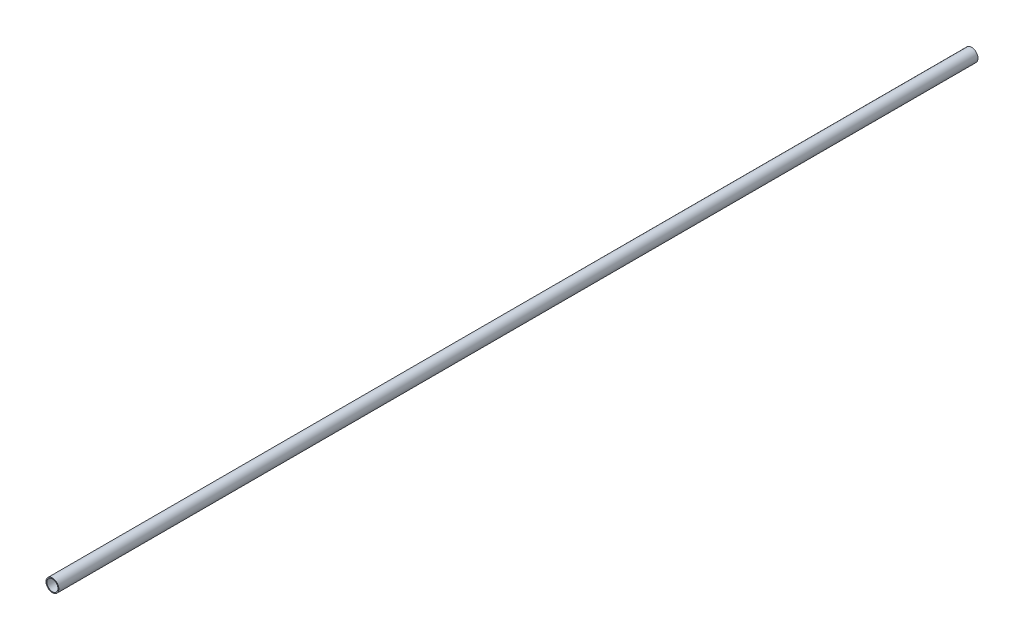
SolidWorks part; units mm, degrees
material "Poltrusion Carbon Fiber"
ref_plane "Front Plane" through (0, 0, 0) normal (0, 0, 1) x (1, 0, 0)
ref_plane "Top Plane" through (0, 0, 0) normal (0, 1, 0) x (1, 0, 0)
ref_plane "Right Plane" through (0, 0, 0) normal (1, 0, 0) x (0, 0, -1)
sketch "Эскиз1" plane through (0, 0, 0) normal (0, 0, 1) x (1, 0, 0)
  circle A0 centre (0, 0) radius 7
  circle A1 centre (0, 0) radius 6
  dimension "D1" = 14
  dimension "D2" = 1
extrude "Бобышка-Вытянуть1" add sketch "Эскиз1" along normal mid plane 1000
